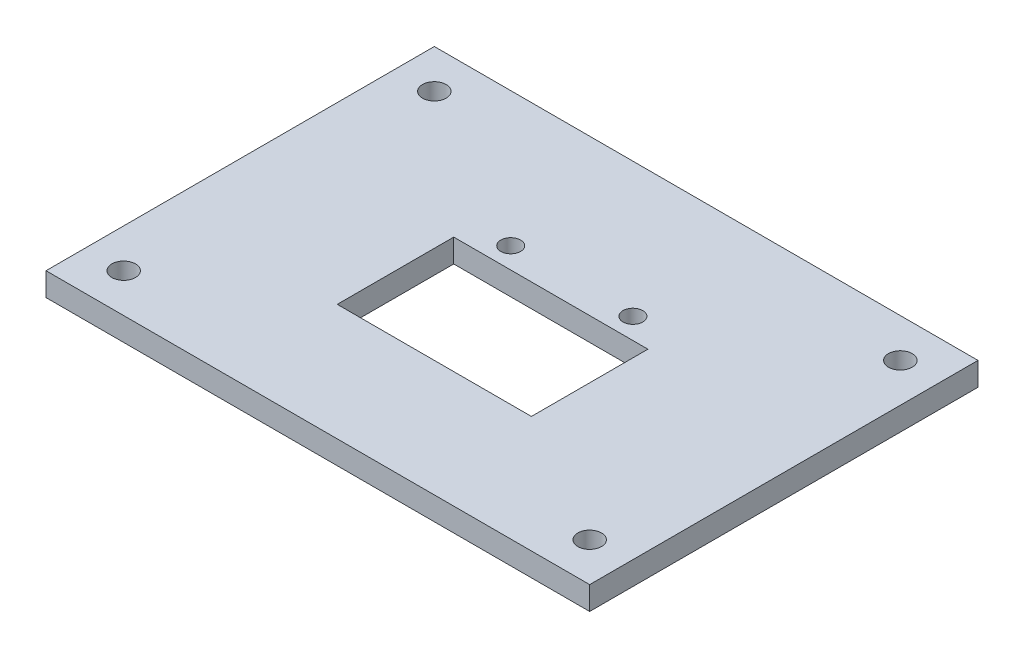
SolidWorks part; units mm, degrees
material "Perspex (TM) GS Acrylic Cast Sheet"
ref_plane "Front Plane" through (0, 0, 0) normal (0, 0, 1) x (1, 0, 0)
ref_plane "Top Plane" through (0, 0, 0) normal (0, 1, 0) x (1, 0, 0)
ref_plane "Right Plane" through (0, 0, 0) normal (1, 0, 0) x (0, 0, -1)
sketch "Sketch1" plane through (0, 0, 0) normal (0, 1, 0) x (1, 0, 0)
  line L1 (0, 0) -> (70, 0)
  line L2 (0, 0) -> (0, 50)
  line L3 (0, 50) -> (70, 50)
  line L4 (70, 0) -> (70, 50)
  dimension "D1" = 50
  dimension "D2" = 70
extrude "Boss-Extrude1" add sketch "Sketch1" along normal blind 3
sketch "Sketch2" plane through (0, 3, 0) normal (0, 1, 0) x (1, 0, 0)
  line L0 (70, 50) -> (0, 50) construction
  line L1 (22.5, 30) -> (47.5, 30)
  line L2 (22.5, 30) -> (22.5, 15)
  line L3 (22.5, 15) -> (47.5, 15)
  line L4 (47.5, 30) -> (47.5, 15)
  line L5 (0, 0) -> (70, 0) construction
  line L6 (35, 30) -> (35, 50) construction
  circle A0 centre (27.135, 32.7) radius 1.275
  circle A1 centre (42.865, 32.7) radius 1.275
  point P4 (35, 50)
  point P5 (35, 30)
  dimension "D4" = 2.55
  dimension "D1" = 15
  dimension "D2" = 25
  dimension "D3" = 15
  dimension "D5" = 2.7
  dimension "D6" = 15.73
extrude "Cut-Extrude1" cut sketch "Sketch2" against normal blind 3
sketch "Sketch3" plane through (0, 3, 0) normal (0, 1, 0) x (1, 0, 0)
  line L0 (35, 50) -> (35, 0) construction
  line L1 (70, 50) -> (0, 50) construction
  line L2 (0, 0) -> (70, 0) construction
  line L4 (70, 0) -> (70, 50) construction
  line L5 (70, 25) -> (0, 25) construction
  line L6 (0, 50) -> (0, 0) construction
  circle A0 centre (5, 45) radius 1.525
  circle A1 centre (65, 45) radius 1.525
  circle A2 centre (65, 5) radius 1.525
  circle A3 centre (5, 5) radius 1.525
  dimension "D3" = 3.05
  dimension "D1" = 5
  dimension "D2" = 5
extrude "Cut-Extrude2" cut sketch "Sketch3" against normal blind 3
